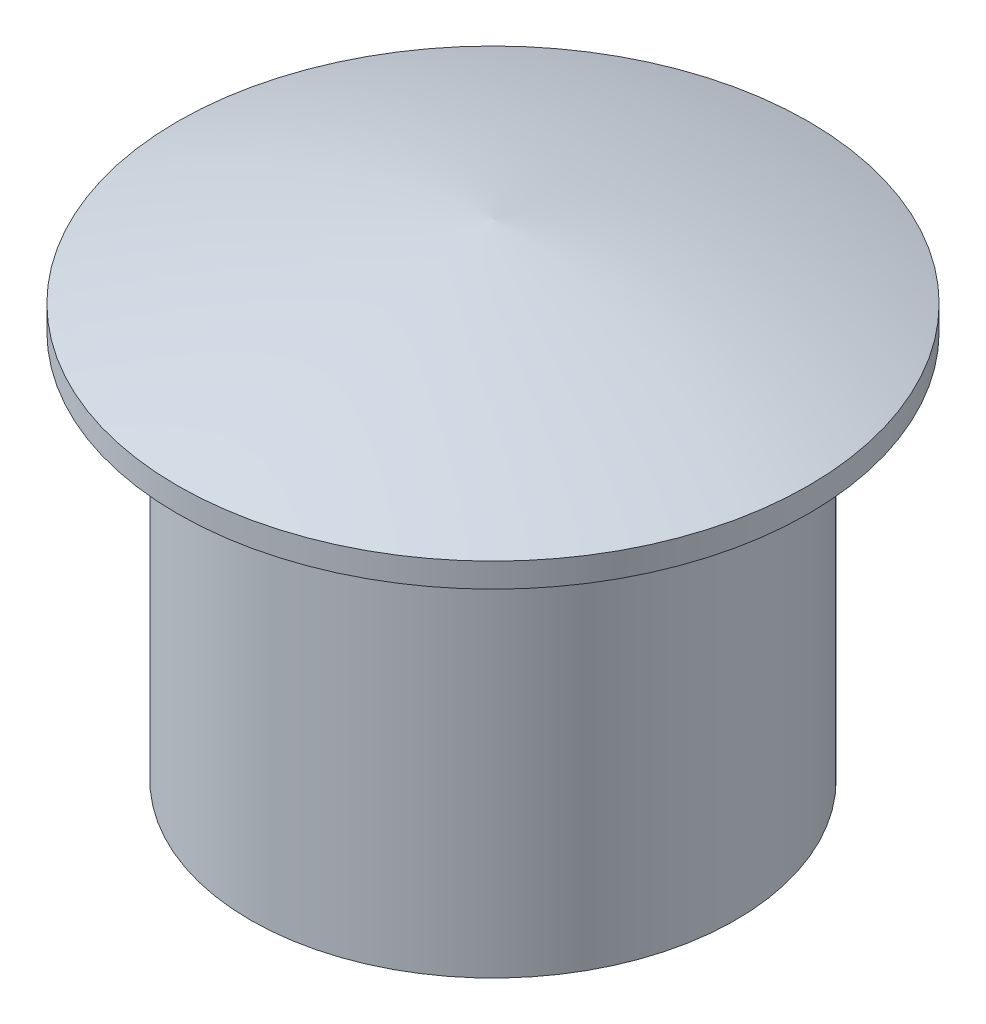
SolidWorks part; units mm, degrees
ref_plane "Front Plane" through (0, 0, 0) normal (0, 0, 1) x (1, 0, 0)
ref_plane "Top Plane" through (0, 0, 0) normal (0, 1, 0) x (1, 0, 0)
ref_plane "Right Plane" through (0, 0, 0) normal (1, 0, 0) x (0, 0, -1)
sketch "Sketch1" plane through (0, 0, 0) normal (0, 0, 1) x (1, 0, 0)
  line L0 (0, 20.1325) -> (0, -26.755) construction
  line L1 (-10, -4) -> (-10, -20)
  line L2 (-10, -4) -> (-13, -4)
  line L3 (-13, -4) -> (-13, -3)
  line L4 (-10, -20) -> (0, -20)
  line L5 (0, -20) -> (0, 0)
  arc A0 (-13, -3) -> (0, 0) centre (6.1635, -56.375) cw
  dimension "D1" = 10
  dimension "D2" = 1
  dimension "D3" = 16
  dimension "D4" = 3
  dimension "D5" = 20
revolve "Revolve1" add sketch "Sketch1" angle 360 about L0
